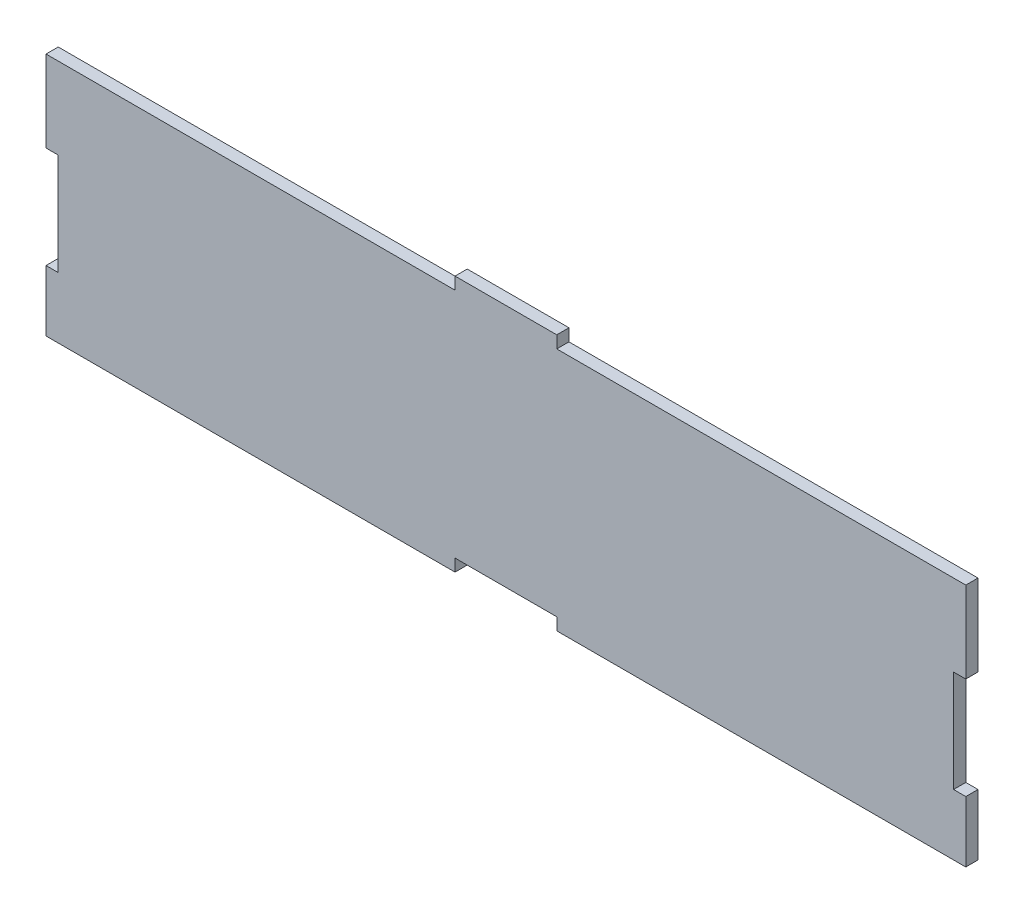
SolidWorks part; units mm, degrees
ref_plane "Спереди" through (0, 0, 0) normal (0, 0, 1) x (1, 0, 0)
ref_plane "Сверху" through (0, 0, 0) normal (0, 1, 0) x (1, 0, 0)
ref_plane "Справа" through (0, 0, 0) normal (1, 0, 0) x (0, 0, -1)
sketch "Эскиз1" plane through (0, 0, 0) normal (0, 0, 1) x (1, 0, 0)
  line L0 (-92.3153, -63.9894) -> (-92.3153, -78.9894)
  line L1 (-92.3153, -18.9894) -> (8.1847, -18.9894)
  line L2 (-92.3153, -18.9894) -> (-92.3153, -38.9894)
  line L3 (-92.3153, -78.9894) -> (8.1847, -78.9894)
  line L4 (133.6847, -18.9894) -> (133.6847, -38.9894)
  line L6 (8.1847, -78.9894) -> (8.1847, -75.9894)
  line L7 (8.1847, -75.9894) -> (33.1847, -75.9894)
  line L8 (33.1847, -78.9894) -> (33.1847, -75.9894)
  line L9 (-92.3153, -38.9894) -> (-89.3153, -38.9894)
  line L11 (-92.3153, -63.9894) -> (-89.3153, -63.9894)
  line L12 (-89.3153, -38.9894) -> (-89.3153, -63.9894)
  line L13 (133.6847, -38.9894) -> (130.6847, -38.9894)
  line L15 (133.6847, -63.9894) -> (130.6847, -63.9894)
  line L16 (130.6847, -38.9894) -> (130.6847, -63.9894)
  line L18 (8.1847, -18.9894) -> (8.1847, -15.9894)
  line L19 (8.1847, -15.9894) -> (33.1847, -15.9894)
  line L20 (33.1847, -18.9894) -> (33.1847, -15.9894)
  line L21 (33.1847, -78.9894) -> (133.6847, -78.9894)
  line L22 (133.6847, -63.9894) -> (133.6847, -78.9894)
  line L23 (33.1847, -18.9894) -> (133.6847, -18.9894)
  dimension "D1" = 226
  dimension "D2" = 60
  dimension "D3" = 25
  dimension "D4" = 25
  dimension "D5" = 25
  dimension "D6" = 25
  dimension "D7" = 3
  dimension "D8" = 3
  dimension "D9" = 3
  dimension "D10" = 3
  dimension "D11" = 100.5
  dimension "D12" = 100.5
  dimension "D13" = 15
  dimension "D14" = 15
extrude "Бобышка-Вытянуть1" add sketch "Эскиз1" along normal blind 3
